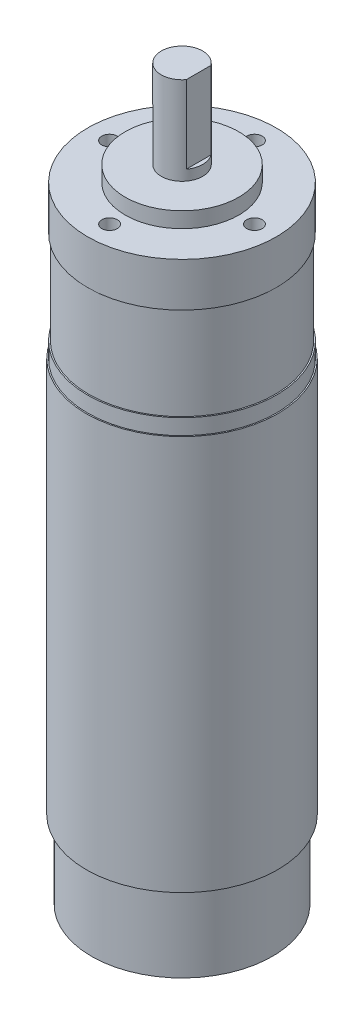
SolidWorks part; units mm, degrees
ref_plane "Plan de face" through (0, 0, 0) normal (0, 0, 1) x (1, 0, 0)
ref_plane "Plan de dessus" through (0, 0, 0) normal (0, 1, 0) x (1, 0, 0)
ref_plane "Plan de droite" through (0, 0, 0) normal (1, 0, 0) x (0, 0, -1)
sketch "Esquisse1" plane through (0, 0, 0) normal (0, 1, 0) x (1, 0, 0)
  circle A0 centre (0, 0) radius 17.492
  dimension "D1" = 34.984
extrude "Extrusion1" add sketch "Esquisse1" along normal blind 15
sketch "Esquisse2" plane through (0, 15, 0) normal (0, 1, 0) x (1, 0, 0)
  circle A0 centre (0, 0) radius 18.491
extrude "Extrusion2" add sketch "Esquisse2" along normal blind 76.339
sketch "Esquisse3" plane through (0, 91.339, 0) normal (0, 1, 0) x (1, 0, 0)
  circle A0 centre (0, 0) radius 18.25
extrude "Extrusion3" add sketch "Esquisse3" along normal blind 3
sketch "Esquisse4" plane through (0, 94.339, 0) normal (0, 1, 0) x (1, 0, 0)
  circle A0 centre (0, 0) radius 18
extrude "Extrusion4" add sketch "Esquisse4" along normal blind 18
sketch "Esquisse5" plane through (0, 112.339, 0) normal (0, 1, 0) x (1, 0, 0)
  circle A0 centre (0, 0) radius 18.241
extrude "Extrusion5" add sketch "Esquisse5" along normal blind 8.5
sketch "Esquisse6" plane through (0, 120.839, 0) normal (0, 1, 0) x (1, 0, 0)
  circle A0 centre (0, 0) radius 10.977
extrude "Extrusion6" add sketch "Esquisse6" along normal blind 3
sketch "Esquisse7" plane through (0, 123.839, 0) normal (0, 1, 0) x (-1, 0, 0)
  circle A0 centre (0, 0) radius 4
extrude "Extrusion7" add sketch "Esquisse7" along normal blind 17
sketch "Esquisse8" plane through (0, 140.839, 0) normal (0, 1, 0) x (1, 0, 0)
  line L1 (5.9036, 5.236) -> (3.212, 5.236)
  line L2 (5.9036, 5.236) -> (5.9036, -7.2968)
  line L3 (5.9036, -7.2968) -> (3.212, -7.2968)
  line L4 (3.212, 5.236) -> (3.212, -7.2968)
  dimension "D1" = 3.212
extrude "Extrusion8" cut sketch "Esquisse8" against normal blind 15
sketch "Esquisse9" plane through (0, 120.839, 0) normal (0, 1, 0) x (1, 0, 0)
  circle A0 centre (0, 14) radius 1.5
  circle A1 centre (14.001, 0.001) radius 1.5
  circle A2 centre (0.002, -14) radius 1.5
  circle A3 centre (-13.999, -0.001) radius 1.5
  dimension "D1" = 14
  dimension "D2" = 3
extrude "Extrusion9" cut sketch "Esquisse9" against normal blind 7
